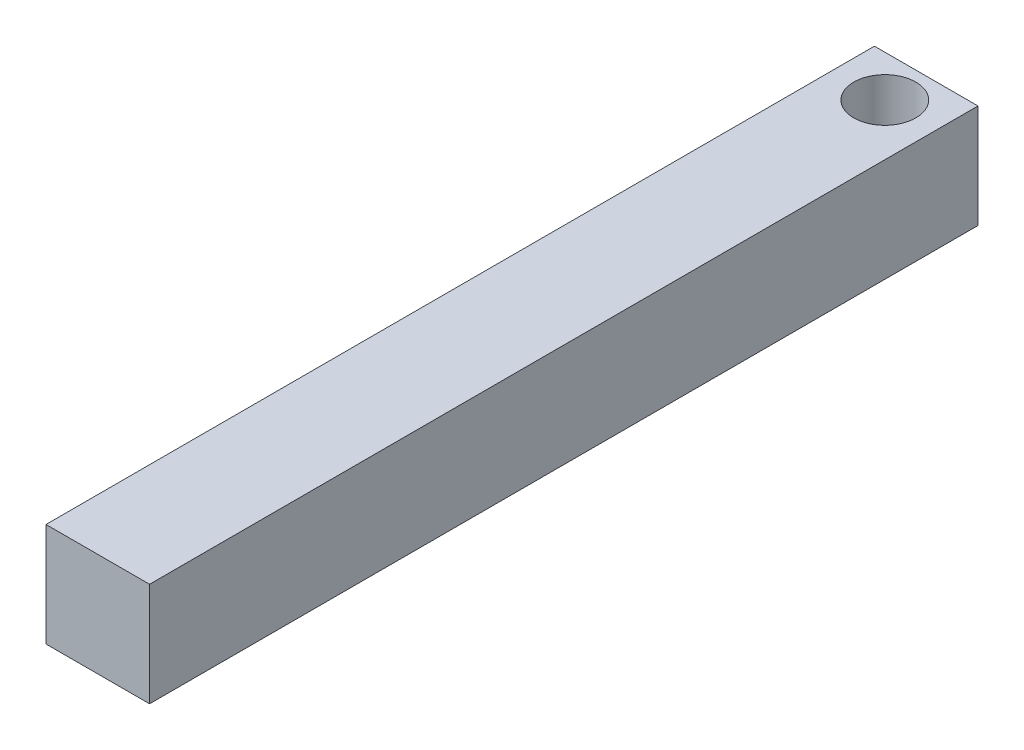
SolidWorks part; units mm, degrees
ref_plane "Front Plane" through (0, 0, 0) normal (0, 0, 1) x (1, 0, 0)
ref_plane "Top Plane" through (0, 0, 0) normal (0, 1, 0) x (1, 0, 0)
ref_plane "Right Plane" through (0, 0, 0) normal (1, 0, 0) x (0, 0, -1)
sketch "Sketch1" plane through (0, 0, 0) normal (0, 0, 1) x (1, 0, 0)
  line L1 (-10, -10) -> (10, -10)
  line L2 (-10, -10) -> (-10, 10)
  line L3 (-10, 10) -> (10, 10)
  line L4 (10, -10) -> (10, 10)
  line L5 (-10, -10) -> (10, 10) construction
  line L6 (-10, 10) -> (10, -10) construction
  line L7 (-9, -9) -> (9, -9) construction
  line L8 (-9, -9) -> (-9, 9) construction
  line L9 (-9, 9) -> (9, 9) construction
  line L10 (9, -9) -> (9, 9) construction
  line L11 (-9, -9) -> (9, 9) construction
  line L12 (-9, 9) -> (9, -9) construction
  point P0 (0, 0)
  point P6 (0, 0)
  dimension "D1" = 20
  dimension "D2" = 20
  dimension "D3" = 1
  dimension "D4" = 1
extrude "Boss-Extrude1" add sketch "Sketch1" along normal blind 160
sketch "Sketch2" plane through (0, 10, 0) normal (0, 1, 0) x (1, 0, 0)
  line L0 (0, 0) -> (0, -160) construction
  line L1 (10, -160) -> (-10, -160) construction
  line L2 (10, 0) -> (-10, 0) construction
  circle A0 centre (0, -8) radius 6
  dimension "D1" = 12
  dimension "D2" = 8
extrude "Cut-Extrude1" cut sketch "Sketch2" against normal blind 100
